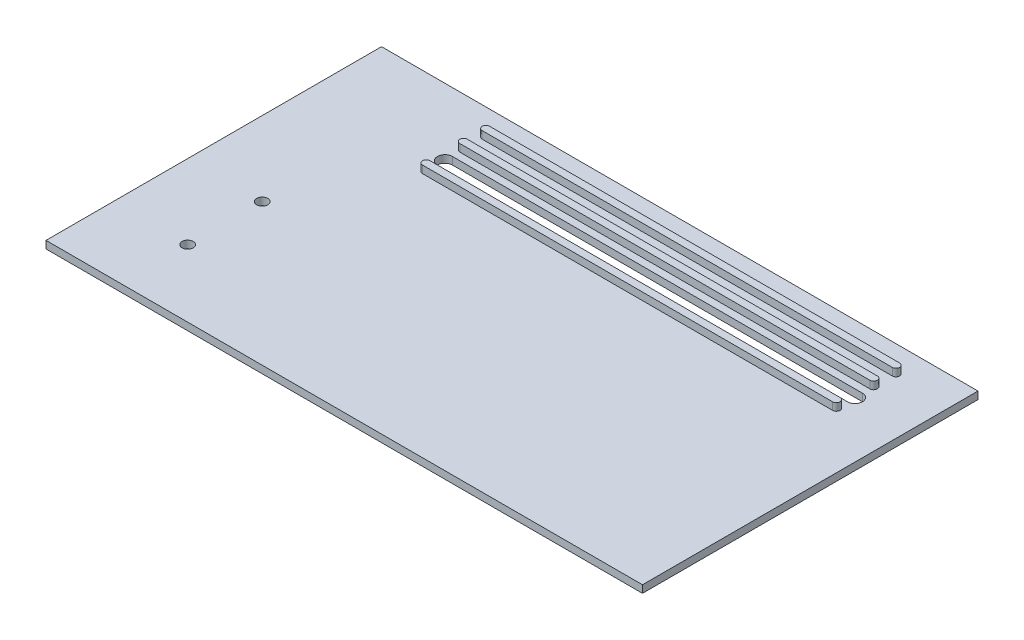
SolidWorks part; units mm, degrees
ref_plane "Front Plane" through (0, 0, 0) normal (0, 0, 1) x (1, 0, 0)
ref_plane "Top Plane" through (0, 0, 0) normal (0, 1, 0) x (1, 0, 0)
ref_plane "Right Plane" through (0, 0, 0) normal (1, 0, 0) x (0, 0, -1)
sketch "Sketch1" plane through (0, 0, 0) normal (0, 1, 0) x (1, 0, 0)
  line L0 (175, 360) -> (725, 360) construction
  line L1 (0, 0) -> (800, 0)
  line L2 (0, 0) -> (0, 450)
  line L3 (0, 450) -> (800, 450)
  line L4 (800, 0) -> (800, 450)
  line L5 (175, 370) -> (725, 370)
  line L6 (175, 350) -> (725, 350)
  line L7 (175, 260) -> (725, 260) construction
  line L8 (175, 270) -> (725, 270) construction
  line L9 (175, 250) -> (725, 250) construction
  line L10 (450, 432.6659) -> (450, 227.7256) construction
  line L11 (175, 90) -> (725, 90) construction
  line L12 (175, 97.5) -> (725, 97.5) construction
  line L13 (175, 82.5) -> (725, 82.5) construction
  circle A0 centre (100, 190) radius 7.5
  circle A1 centre (100, 90) radius 7.5
  arc A2 (175, 370) -> (175, 350) centre (175, 360) ccw
  arc A3 (725, 350) -> (725, 370) centre (725, 360) ccw
  arc A4 (175, 270) -> (175, 250) centre (175, 260) ccw construction
  arc A5 (725, 250) -> (725, 270) centre (725, 260) ccw construction
  arc A6 (175, 97.5) -> (175, 82.5) centre (175, 90) ccw construction
  arc A7 (725, 82.5) -> (725, 97.5) centre (725, 90) ccw construction
  point P10 (450, 360)
  point P17 (450, 260)
  point P26 (450, 90)
  dimension "D3" = 15
  dimension "D4" = 15
  dimension "D8" = 10
  dimension "D1" = 800
  dimension "D2" = 450
  dimension "D5" = 100
  dimension "D6" = 100
  dimension "D7" = 90
  dimension "D9" = 550
  dimension "D10" = 350
  dimension "D11" = 170
  dimension "D12" = 100
  dimension "D13" = 15
  dimension "D14" = 550
extrude "Boss-Extrude1" add sketch "Sketch1" along normal blind 10
sketch "Sketch2" plane through (0, 10, 0) normal (0, 1, 0) x (1, 0, 0)
  line L0 (450, 385) -> (450, 335) construction
  line L1 (175, 385) -> (725, 385) construction
  line L2 (175, 390) -> (725, 390)
  line L3 (175, 380) -> (725, 380)
  line L4 (175, 335) -> (725, 335) construction
  line L5 (175, 340) -> (725, 340)
  line L6 (175, 330) -> (725, 330)
  line L7 (725, 370) -> (175, 370) construction
  line L8 (175, 350) -> (725, 350) construction
  line L9 (175, 415) -> (725, 415) construction
  line L10 (175, 420) -> (725, 420)
  line L11 (175, 410) -> (725, 410)
  arc A0 (175, 390) -> (175, 380) centre (175, 385) ccw
  arc A1 (725, 380) -> (725, 390) centre (725, 385) ccw
  arc A2 (175, 340) -> (175, 330) centre (175, 335) ccw
  arc A3 (725, 330) -> (725, 340) centre (725, 335) ccw
  arc A5 (175, 420) -> (175, 410) centre (175, 415) ccw
  arc A6 (725, 410) -> (725, 420) centre (725, 415) ccw
  point P3 (450, 385)
  point P11 (450, 335)
  point P22 (450, 370)
  point P25 (450, 415)
  dimension "D1" = 550
  dimension "D2" = 10
  dimension "D3" = 10
  dimension "D4" = 10
  dimension "D5" = 20
extrude "Boss-Extrude2" add sketch "Sketch2" along normal blind 10
